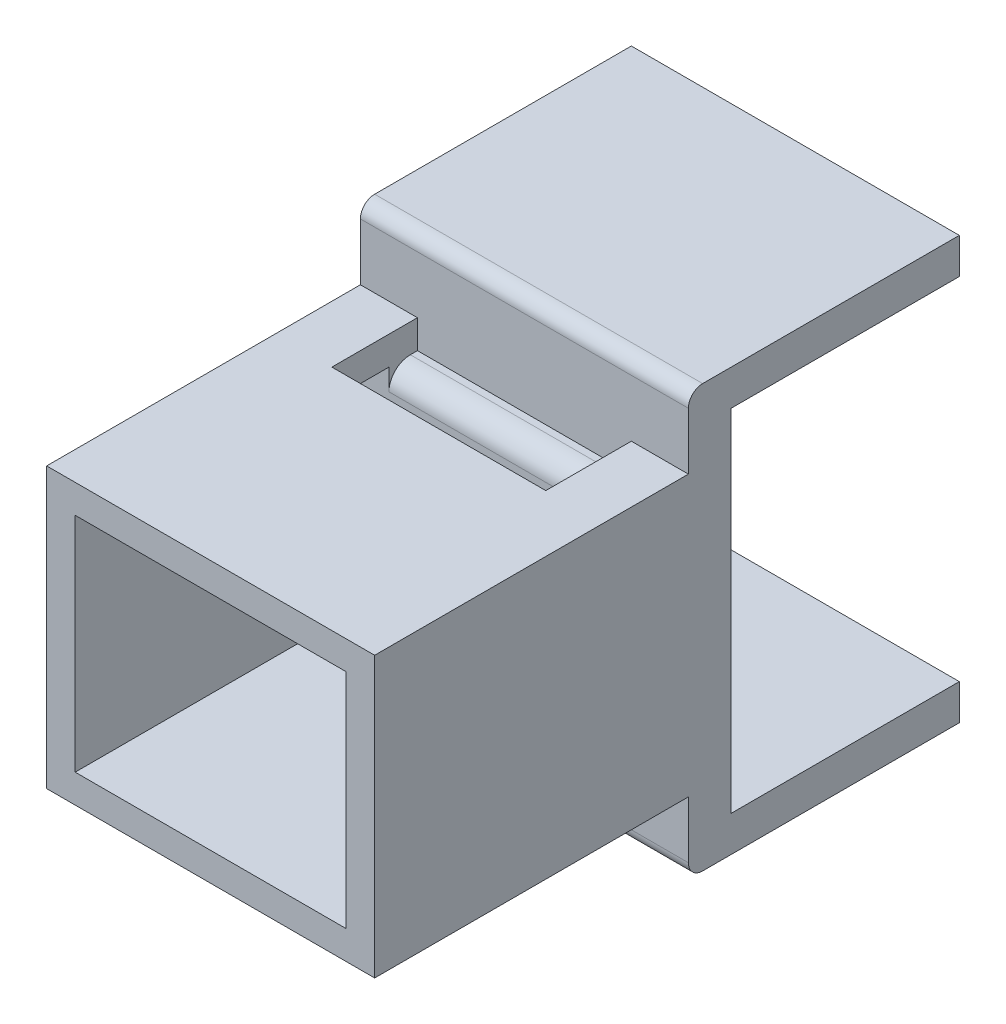
SolidWorks part; units mm, degrees
ref_plane "Plan de face" through (0, 0, 0) normal (0, 0, 1) x (1, 0, 0)
ref_plane "Plan de dessus" through (0, 0, 0) normal (0, 1, 0) x (1, 0, 0)
ref_plane "Plan de droite" through (0, 0, 0) normal (1, 0, 0) x (0, 0, -1)
sketch "Esquisse1" plane through (0, 0, 0) normal (0, 0, 1) x (1, 0, 0)
  line L1 (0, 0) -> (11.5, 0)
  line L2 (0, 0) -> (0, 9.8)
  line L3 (0, 9.8) -> (11.5, 9.8)
  line L4 (11.5, 0) -> (11.5, 9.8)
  dimension "D1" = 11.5
  dimension "D2" = 9.8
extrude "Boss.-Extru.1" add sketch "Esquisse1" along normal blind 11
sketch "Esquisse2" plane through (0, 0, 11) normal (0, 0, 1) x (1, 0, 0)
  line L0 (0, 9.8) -> (0, 0) construction
  line L1 (1, 1) -> (10.5, 1)
  line L2 (1, 1) -> (1, 8.8)
  line L3 (1, 8.8) -> (10.5, 8.8)
  line L4 (10.5, 1) -> (10.5, 8.8)
  line L5 (0, 0) -> (11.5, 0) construction
  line L6 (11.5, 0) -> (11.5, 9.8) construction
  line L7 (11.5, 9.8) -> (0, 9.8) construction
  dimension "D1" = 1
  dimension "D2" = 1
  dimension "D3" = 1
  dimension "D4" = 1
extrude "Enlèv. mat.-Extru.1" cut sketch "Esquisse2" against normal blind 10
sketch "Esquisse3" plane through (0, 9.8, 0) normal (0, 1, 0) x (1, 0, 0)
  line L0 (11.5, 0) -> (0, 0) construction
  line L1 (2, 0) -> (9.5, 0)
  line L2 (2, 0) -> (2, -3)
  line L3 (2, -3) -> (9.5, -3)
  line L4 (9.5, 0) -> (9.5, -3)
  line L5 (0, -11) -> (0, 0) construction
  line L6 (11.5, -11) -> (11.5, 0) construction
  dimension "D1" = 0
  dimension "D2" = 2
  dimension "D3" = 2
  dimension "D4" = 3
extrude "Enlèv. mat.-Extru.2" cut sketch "Esquisse3" against normal blind 1
fillet "Congé1" radius 0.75 2 edges at (5.75, 8.8, 1) (5.75, 8.8, 3)
sketch "Esquisse4" plane through (0, 0, 0) normal (0, 0, -1) x (-1, 0, 0)
  line L0 (-11.5, 0) -> (-11.5, 9.8) construction
  line L1 (-11.5, -2.5) -> (0, -2.5)
  line L2 (-11.5, -2.5) -> (-11.5, 12.3)
  line L3 (-11.5, 12.3) -> (0, 12.3)
  line L4 (0, -2.5) -> (0, 12.3)
  line L5 (0, 9.8) -> (0, 0) construction
  line L6 (0, 0) -> (-11.5, 0) construction
  line L7 (-11.5, 9.8) -> (-9.5, 9.8) construction
  dimension "D1" = 0
  dimension "D2" = 0
  dimension "D3" = 2.5
  dimension "D4" = 2.5
  dimension "D5" = 14.8
extrude "Boss.-Extru.2" add sketch "Esquisse4" along normal blind 1.5
sketch "Esquisse5" plane through (0, 0, -1.5) normal (0, 0, -1) x (-1, 0, 0)
  line L0 (-11.5, 12.3) -> (-11.5, -2.5) construction
  line L1 (-11.5, 11.05) -> (0, 11.05)
  line L2 (-11.5, 11.05) -> (-11.5, 12.3)
  line L3 (-11.5, 12.3) -> (0, 12.3)
  line L4 (0, 11.05) -> (0, 12.3)
  line L5 (0, -2.5) -> (0, 12.3) construction
  line L6 (0, 12.3) -> (-11.5, 12.3) construction
  line L7 (-11.5, -2.5) -> (0, -2.5)
  line L8 (-11.5, -2.5) -> (-11.5, -1.25)
  line L9 (-11.5, -1.25) -> (0, -1.25)
  line L10 (0, -2.5) -> (0, -1.25)
  line L11 (-11.5, -2.5) -> (0, -2.5) construction
  dimension "D1" = 0
  dimension "D2" = 0
  dimension "D3" = 0
  dimension "D4" = 1.25
  dimension "D5" = 0
  dimension "D6" = 0
  dimension "D7" = 1.25
extrude "Boss.-Extru.3" add sketch "Esquisse5" along normal blind 8
fillet "Congé2" radius 0.5 2 edges at (5.75, -2.5, 0) (5.75, 12.3, 0)
